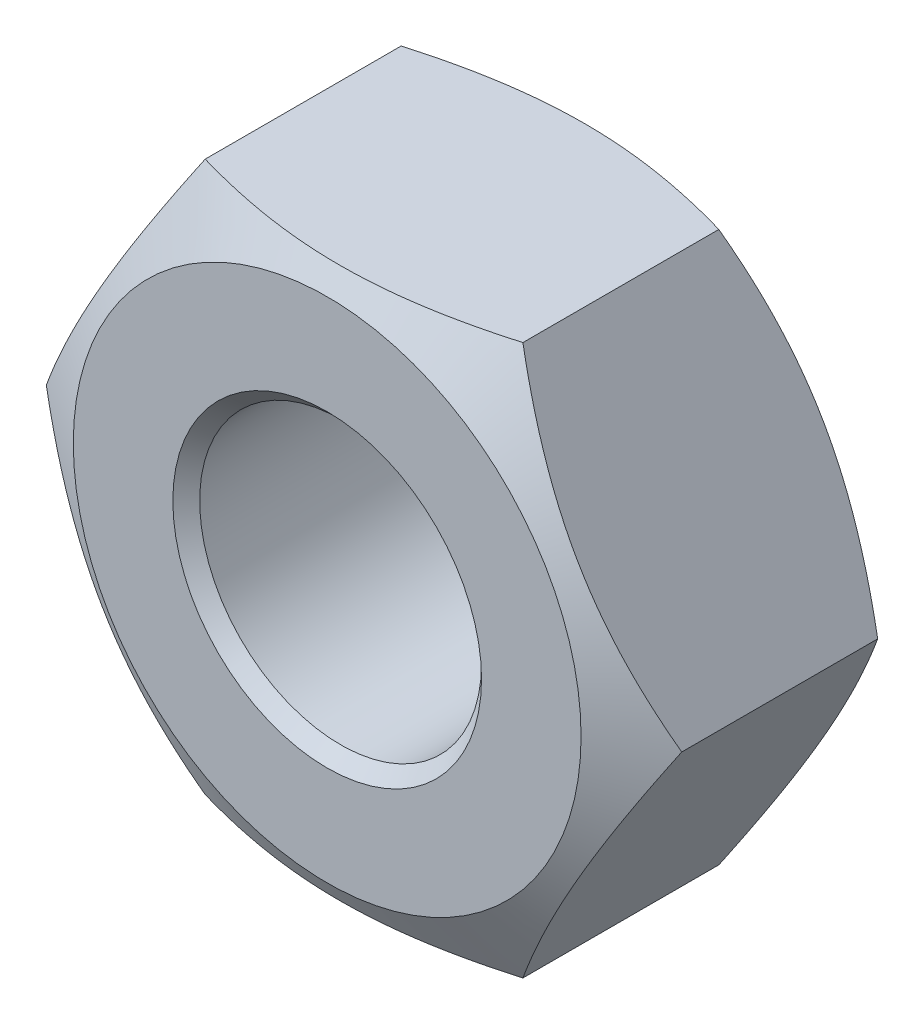
SolidWorks part; units mm, degrees
ref_plane "Front" through (0, 0, 0) normal (0, 0, 1) x (1, 0, 0)
ref_plane "Top" through (0, 0, 0) normal (0, 1, 0) x (1, 0, 0)
ref_plane "Right" through (0, 0, 0) normal (1, 0, 0) x (0, 0, -1)
sketch "Sketch1" plane through (0, 0, 0) normal (0, 0, 1) x (1, 0, 0)
  line L0 (0, 12.5388) -> (0, -12.5388) construction
  line L1 (-16.6249, 0) -> (17.6622, 0) construction
  line L3 (23.6714, 0) -> (11.8357, 20.5)
  line L4 (11.8357, 20.5) -> (-11.8357, 20.5)
  line L5 (-11.8357, 20.5) -> (-23.6714, 0)
  line L6 (-23.6714, 0) -> (-11.8357, -20.5)
  line L7 (-11.8357, -20.5) -> (11.8357, -20.5)
  line L8 (11.8357, -20.5) -> (23.6714, 0)
  circle A1 centre (0, 0) radius 20.5 construction
  dimension "D1" = 41
extrude "Base-Extrude" add sketch "Sketch1" along normal blind 20
sketch "Szkic1" plane through (0, 0, 20) normal (0, 0, 1) x (1, 0, 0)
  line L0 (-11.8357, 20.5) -> (11.8357, -20.5) construction
  line L1 (11.8357, 20.5) -> (-11.8357, -20.5) construction
  circle A0 centre (0, 0) radius 18.916
extrude "Wytnij-wyciągnięcie1" cut sketch "Szkic1" against normal blind 3 draft 60 flip side to cut
sketch "Szkic2" plane through (0, 0, 0) normal (0, 0, -1) x (-1, 0, 0)
  line L0 (11.8357, -20.5) -> (-11.8357, 20.5) construction
  line L1 (-11.8357, -20.5) -> (11.8357, 20.5) construction
  circle A0 centre (0, 0) radius 19.0689
extrude "Wytnij-wyciągnięcie2" cut sketch "Szkic2" against normal blind 3 draft 60 flip side to cut
hole_wizard "Otwór gwintowany M241" positions "Szkic4" profile "Szkic3" tap size "M24" standard "ISO" end condition up to next
sketch "Szkic4" plane through (0, 0, 0) normal (0, 0, -1) x (-1, 0, 0)
  point P0 (0, 0)
sketch "Szkic3" plane through (0, 0, 0) normal (1, 0, 0) x (0, 1, 0)
  line L0 (0, 0) -> (0, 20)
  line L1 (0, 20) -> (10.5, 20)
  line L2 (10.5, 20) -> (10.5, 0)
  line L5 (10.5, 0) -> (0, 0)
  line L11 (0, -6.35) -> (0, 107.95) construction
  dimension "Średnica otworu gwintowanego na wylot" = 21
  dimension "Głębokość otworu gwintowanego na wylot" = 20
cosmetic thread "Gwint otworu1" parameters "D2"=24
chamfer "Sfazowanie1" distance 1 angle 45 2 edges at (10.5, 0, 20) (-10.5, 0, 0)
